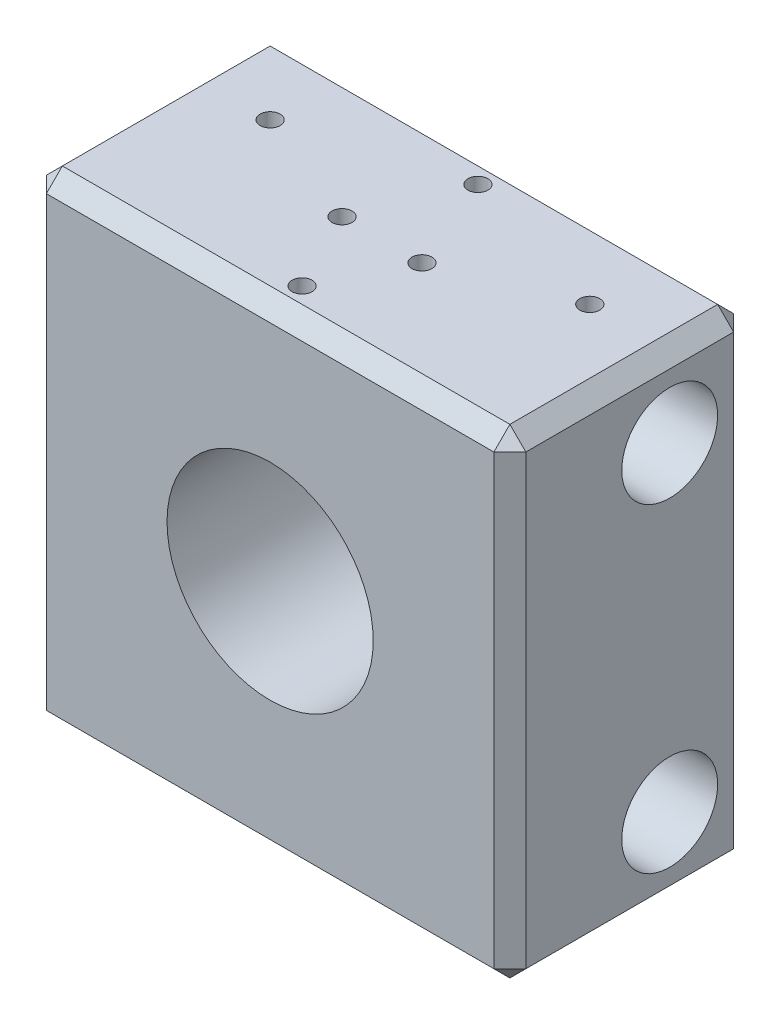
SolidWorks part; units mm, degrees
ref_plane "Front Plane" through (0, 0, 0) normal (0, 0, 1) x (1, 0, 0)
ref_plane "Top Plane" through (0, 0, 0) normal (0, 1, 0) x (1, 0, 0)
ref_plane "Right Plane" through (0, 0, 0) normal (1, 0, 0) x (0, 0, -1)
sketch "Sketch1" plane through (0, 0, 0) normal (0, 0, 1) x (1, 0, 0)
  line L1 (-30, 30) -> (30, 30)
  line L2 (-30, 30) -> (-30, -30)
  line L3 (-30, -30) -> (30, -30)
  line L4 (30, 30) -> (30, -30)
  line L5 (-30, 30) -> (30, -30) construction
  line L6 (-30, -30) -> (30, 30) construction
  circle A0 centre (0, 0) radius 12.9
  point P0 (0, 0)
extrude "Boss-Extrude1" add sketch "Sketch1" along normal blind 30
sketch "Sketch2" plane through (30, 0, 0) normal (1, 0, 0) x (0, 0, -1)
  line L0 (-15, 30) -> (-15, -30) construction
  line L1 (-30, 30) -> (0, 30) construction
  line L2 (-30, -30) -> (0, -30) construction
  line L3 (-15, 0) -> (-15, 20) construction
  line L4 (-15, 0) -> (-15, -20) construction
  line L5 (-10, 30) -> (-10, -30)
  circle A0 centre (-10, 20) radius 6
  circle A1 centre (-10, -20) radius 6
  dimension "D1" = 5
extrude "Cut-Extrude1" cut sketch "Sketch2" against normal blind 70 contours L5 A0 | L5 A0 | L5 A1 | L5 A1
sketch "Sketch3" plane through (0, 30, 0) normal (0, 1, 0) x (1, 0, 0)
  line L0 (30, -4) -> (30, -16) construction
  line L1 (-30, -4) -> (-30, -16) construction
  line L2 (-30, -10) -> (30, -10) construction
  line L3 (30, -10) -> (20, -10) construction
  line L4 (-30, -10) -> (-20, -10) construction
  circle A0 centre (20, -10) radius 1.25
  circle A1 centre (-20, -10) radius 1.25
extrude "Cut-Extrude2" cut sketch "Sketch3" against normal blind 10 contours A1 | A0
sketch "Sketch4" plane through (0, 30, 0) normal (0, 1, 0) x (1, 0, 0)
  line L0 (-30, -16) -> (-10, -16) construction
  line L1 (-30, -16) -> (30, -16) construction
  line L2 (-10, -16) -> (10, -16) construction
  line L3 (-10, -16) -> (-5, -16) construction
  line L4 (10, -16) -> (5, -16) construction
  circle A0 centre (-5, -16) radius 1.25
  circle A1 centre (5, -16) radius 1.25
extrude "Cut-Extrude3" cut sketch "Sketch4" against normal blind 30
sketch "Sketch5" plane through (0, 30, 0) normal (0, 1, 0) x (1, 0, 0)
  line L0 (0, -30) -> (0, -26) construction
  line L1 (30, -30) -> (-30, -30) construction
  line L2 (0, 0) -> (0, -4) construction
  line L3 (30, -4) -> (-30, -4) construction
  circle A0 centre (0, -26) radius 1.25
  circle A1 centre (0, -4) radius 1.25
extrude "Cut-Extrude4" cut sketch "Sketch5" against normal blind 30 contours A1 | A0
sketch "Sketch6" plane through (0, -30, 0) normal (0, -1, 0) x (-1, 0, 0)
  line L0 (0, -16) -> (0, -4) construction
  line L1 (-30, -16) -> (30, -16) construction
  line L2 (30, -4) -> (-30, -4) construction
  circle A0 centre (0, -10) radius 1.25
extrude "Cut-Extrude5" cut sketch "Sketch6" against normal blind 10
chamfer "Chamfer2" distance 2 angle 45 12 edges at (30, 30, 15) (0, 30, 30) (0, 30, 0) (-30, 30, 15) (0, -30, 30) (30, 0, 30) (30, -30, 15) (-30, 0, 30) (-30, -30, 15) (30, 0, 0) (0, -30, 0) (-30, 0, 0)
